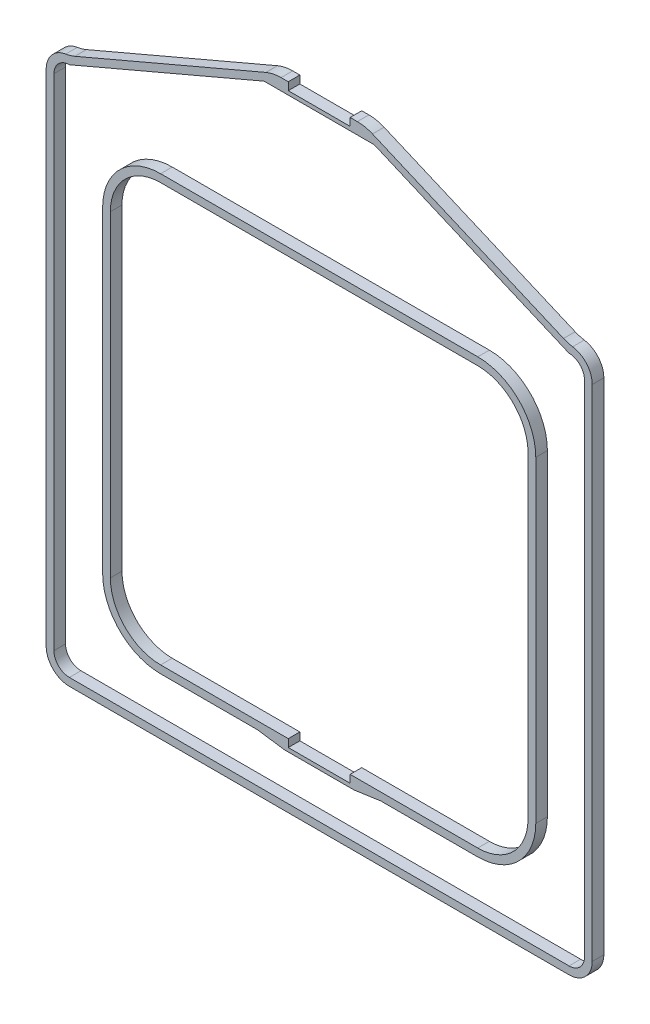
SolidWorks part; units mm, degrees
ref_plane "Front Plane" through (0, 0, 0) normal (0, 0, 1) x (1, 0, 0)
ref_plane "Top Plane" through (0, 0, 0) normal (0, 1, 0) x (1, 0, 0)
ref_plane "Right Plane" through (0, 0, 0) normal (1, 0, 0) x (0, 0, -1)
sketch "Sketch2" plane through (0, 0, 0) normal (0, 0, 1) x (1, 0, 0)
  line L0 (0, -56) -> (0, -57)
  line L1 (-14.2422, 90.1) -> (14.2422, 90.1)
  line L2 (0, -57) -> (9, -57)
  line L3 (9, -57) -> (15.9282, -56)
  line L5 (0, -57) -> (-9, -57)
  line L6 (-9, -57) -> (-15.9282, -56)
  line L7 (-41, -56) -> (-15.9282, -56)
  line L8 (15.9282, -56) -> (41, -56)
  point P0 (0, 54)
  point P1 (-54, 0)
  line B0 (-6, 91.1) -> (-11.9, 91.1)
  line B1 (-11.9, 91.1) -> (-64.6, 68.6)
  line B2 (-68.6, 64.6) -> (-68.6, -64.6)
  line B3 (-64.6, -68.6) -> (64.6, -68.6)
  line B4 (68.6, -64.6) -> (68.6, 64.6)
  line B5 (64.6, 68.6) -> (11.9, 91.1)
  line B6 (11.9, 91.1) -> (6, 91.1)
  line B7 (-56, 41) -> (-56, -41)
  line B8 (41, 56) -> (-41, 56)
  line B9 (56, -41) -> (56, 41)
  line B10 (-70.6, 64.6) -> (-70.6, -64.6)
  line B11 (-13.7811, 92.2969) -> (-63.1825, 71.2052)
  line B12 (9.8546, 93.1) -> (-9.8546, 93.1)
  line B13 (63.1825, 71.2052) -> (13.7811, 92.2969)
  line B14 (70.6, -64.6) -> (70.6, 64.6)
  line B15 (-64.6, -70.6) -> (64.6, -70.6)
  line B16 (-41, -54) -> (41, -54)
  line B17 (54, -41) -> (54, 41)
  line B18 (41, 54) -> (-41, 54)
  line B19 (-54, 41) -> (-54, -41)
  arc B20 (-64.6, 68.6) -> (-68.6, 64.6) centre (-64.6, 64.6) ccw
  arc B21 (-68.6, -64.6) -> (-64.6, -68.6) centre (-64.6, -64.6) ccw
  arc B22 (64.6, -68.6) -> (68.6, -64.6) centre (64.6, -64.6) ccw
  arc B23 (68.6, 64.6) -> (64.6, 68.6) centre (64.6, 64.6) ccw
  arc B24 (-41, 56) -> (-56, 41) centre (-41, 41) ccw
  arc B25 (56, 41) -> (41, 56) centre (41, 41) ccw
  arc B26 (41, -56) -> (56, -41) centre (41, -41) ccw
  arc B27 (-56, -41) -> (-41, -56) centre (-41, -41) ccw
  arc B28 (-70.6, -64.6) -> (-64.6, -70.6) centre (-64.6, -64.6) ccw
  arc B29 (-65.5409, 70.5258) -> (-70.6, 64.6) centre (-64.6, 64.6) ccw
  arc B30 (-65.5409, 70.5258) -> (-63.1825, 71.2052) centre (-67.1091, 80.402) ccw
  arc B31 (-9.8546, 93.1) -> (-13.7811, 92.2969) centre (-9.8546, 83.1) ccw
  arc B32 (13.7811, 92.2969) -> (9.8546, 93.1) centre (9.8546, 83.1) ccw
  arc B33 (63.1825, 71.2052) -> (65.5409, 70.5258) centre (67.1091, 80.402) ccw
  arc B34 (70.6, 64.6) -> (65.5409, 70.5258) centre (64.6, 64.6) ccw
  arc B35 (64.6, -70.6) -> (70.6, -64.6) centre (64.6, -64.6) ccw
  arc B36 (-54, -41) -> (-41, -54) centre (-41, -41) ccw
  arc B37 (41, -54) -> (54, -41) centre (41, -41) ccw
  arc B38 (54, 41) -> (41, 54) centre (41, 41) ccw
  arc B39 (-41, 54) -> (-54, 41) centre (-41, 41) ccw
  dimension "D1" = 1
  dimension "D2" = 18
  dimension "D3" = 1
  dimension "D4" = 7
sketch_block_instance "Layer2-1"
sketch_block "Layer2"
extrude "Boss-Extrude1" add sketch "Sketch2" along normal blind 3
sketch "Sketch3" plane through (0, 0, 3) normal (0, 0, 1) x (1, 0, 0)
  line L0 (-6, 93.1) -> (6, 93.1)
  line L5 (6, 91.1) -> (-6, 91.1)
  line L6 (9.8546, 93.1) -> (-9.8546, 93.1) construction
  line L7 (-8, 93.1) -> (-6, 93.1)
  line L8 (-8, 93.1) -> (-8, 91.1)
  line L9 (-8, 91.1) -> (-6, 91.1)
  line L10 (-6, 93.1) -> (-6, 91.1) construction
  line L12 (-6, 92.1) -> (6, 92.1) construction
  line L13 (6, 93.1) -> (8, 93.1)
  line L14 (6, 93.1) -> (6, 91.1) construction
  line L15 (6, 91.1) -> (8, 91.1)
  line L16 (8, 93.1) -> (8, 91.1)
  point P14 (0, 92.1)
  point P20 (-23.4182, -56)
  point P21 (8, -54)
  dimension "D1" = 12
  dimension "D2" = 2
extrude "Cut-Extrude1" cut sketch "Sketch3" against normal through all
sketch "Sketch4" plane through (0, 0, 3) normal (0, 0, 1) x (1, 0, 0)
  line L0 (-41, -54) -> (41, -54) construction
  line L1 (-8, -54) -> (8, -54)
  line L2 (-8, -54) -> (-8, -56)
  line L3 (-8, -56) -> (8, -56)
  line L4 (8, -54) -> (8, -56)
  point P6 (0, -54)
  dimension "D1" = 16
  dimension "D2" = 2
extrude "Cut-Extrude2" cut sketch "Sketch4" against normal through all
